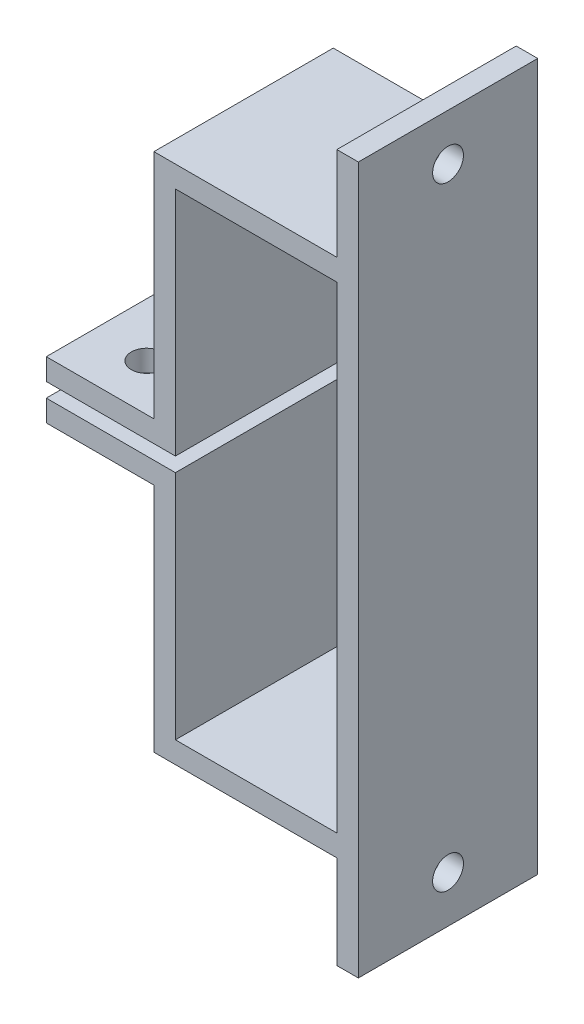
SolidWorks part; units mm, degrees
ref_plane "Front Plane" through (0, 0, 0) normal (0, 0, 1) x (1, 0, 0)
ref_plane "Top Plane" through (0, 0, 0) normal (0, 1, 0) x (1, 0, 0)
ref_plane "Right Plane" through (0, 0, 0) normal (1, 0, 0) x (0, 0, -1)
sketch "Sketch2" plane through (0, 0, 0) normal (0, 0, 1) x (1, 0, 0)
  line L0 (0, 0) -> (0, -72.5)
  line L1 (0, -72.5) -> (-28.5, -72.5)
  line L2 (-28.5, -72.5) -> (-28.5, -40.25)
  line L3 (-28.5, -40.25) -> (-43.5, -40.25)
  line L4 (-43.5, -40.25) -> (-43.5, -37.25)
  line L5 (-43.5, -37.25) -> (-25.5, -37.25)
  line L6 (-25.5, -37.25) -> (-25.5, -69.5)
  line L7 (-25.5, -69.5) -> (-3, -69.5)
  line L8 (-3, -69.5) -> (-3, -3)
  line L9 (-3, -3) -> (-25.5, -3)
  line L10 (-25.5, -3) -> (-25.5, -35.25)
  line L11 (-25.5, -35.25) -> (-43.5, -35.25)
  line L13 (-28.5, 0) -> (0, 0)
  line L14 (-28.5, 0) -> (-28.5, -32.25)
  line L15 (-28.5, -32.25) -> (-43.5, -32.25)
  line L16 (-43.5, -35.25) -> (-43.5, -32.25)
  line L17 (0, -36.25) -> (-58.7559, -36.25) construction
  dimension "D1" = 66.5
  dimension "D2" = 3
  dimension "D3" = 3
  dimension "D4" = 3
  dimension "D5" = 3
  dimension "D6" = 3
  dimension "D7" = 3
  dimension "D8" = 3
  dimension "D9" = 22.5
  dimension "D10" = 15
  dimension "D11" = 1
  dimension "D12" = 1
extrude "Boss-Extrude1" add sketch "Sketch2" along normal blind 25
sketch "Sketch3" plane through (0, 0, 0) normal (1, 0, 0) x (0, 0, -1)
  line L1 (-25, 0) -> (0, 0)
  line L2 (-25, 0) -> (-25, 13)
  line L3 (-25, 13) -> (0, 13)
  line L4 (0, 0) -> (0, 13)
  line L6 (-25, 0) -> (0, 0) construction
  line L7 (-25, -72.5) -> (0, -72.5) construction
  line L8 (-25, -72.5) -> (0, -72.5)
  line L9 (-25, -72.5) -> (-25, -85.5)
  line L10 (-25, -85.5) -> (0, -85.5)
  line L11 (0, -72.5) -> (0, -85.5)
  line L12 (0, -72.5) -> (0, 0) construction
  dimension "D1" = 25
  dimension "D3" = 13
  dimension "D4" = 13
  dimension "D5" = 25
extrude "Boss-Extrude2" add sketch "Sketch3" against normal blind 3
sketch "Sketch4" plane through (-3, 0, 0) normal (-1, 0, 0) x (0, 0, 1)
  line L0 (25, 0) -> (0, 0) construction
  line L1 (0, 0) -> (0, 13) construction
  line L3 (0, -85.5) -> (0, -72.5) construction
  line L4 (25, -85.5) -> (0, -85.5) construction
  circle A0 centre (12.5, 6.5) radius 2.15
  circle A1 centre (12.5, -79) radius 2.15
  dimension "D1" = 4.3
  dimension "D2" = 4.3
  dimension "D3" = 6.5
  dimension "D4" = 12.5
  dimension "D5" = 12.5
  dimension "D6" = 6.5
extrude "Cut-Extrude1" cut sketch "Sketch4" against normal blind 3
sketch "Sketch5" plane through (0, -32.25, 0) normal (0, 1, 0) x (1, 0, 0)
  line L0 (-43.5, -25) -> (-43.5, 0) construction
  line L1 (-43.5, -12.5) -> (-34.3826, -12.5) construction
  circle A0 centre (-36, -6.5) radius 2.15
  circle A1 centre (-36, -18.5) radius 2.15
  dimension "D1" = 4.3
  dimension "D2" = 4.3
  dimension "D3" = 7.5
  dimension "D4" = 6
  dimension "D5" = 6
extrude "Cut-Extrude2" cut sketch "Sketch5" against normal through all both and the other way through all
equation "\"D3@Sketch2\"=\"D2@Sketch2\""
equation "\"D4@Sketch2\"=\"D2@Sketch2\""
equation "\"D5@Sketch2\"=\"D2@Sketch2\""
equation "\"D6@Sketch2\"=\"D2@Sketch2\""
equation "\"D7@Sketch2\"=\"D2@Sketch2\""
equation "\"D8@Sketch2\"=\"D2@Sketch2\""
equation "\"D5@Sketch4\"=\"D4@Sketch4\""
